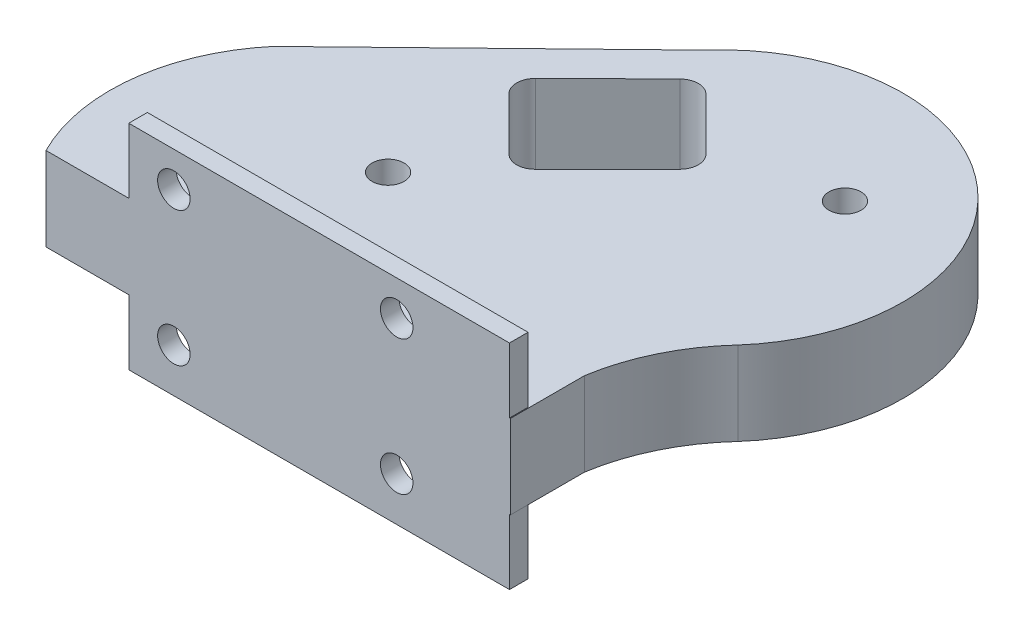
SolidWorks part; units mm, degrees
ref_plane "Front Plane" through (0, 0, 0) normal (0, 0, 1) x (1, 0, 0)
ref_plane "Top Plane" through (0, 0, 0) normal (0, 1, 0) x (1, 0, 0)
ref_plane "Right Plane" through (0, 0, 0) normal (1, 0, 0) x (0, 0, -1)
sketch "Sketch1" plane through (0, 0, 0) normal (0, 1, 0) x (1, 0, 0)
  line L0 (0, 0) -> (50, 0)
  line L1 (2.5356, 21.9463) -> (26.2158, 44.9299)
  line L2 (50, 0) -> (50, 8)
  arc A0 (0, 0) -> (2.5356, 21.9463) centre (17.8501, 9.0572) cw
  arc A1 (26.2158, 44.9299) -> (55.3976, 19.1107) centre (40.8067, 32.0203) cw
  arc A4 (50, 8) -> (55.3976, 19.1107) centre (71.1751, 4.5796) cw
  dimension "D1" = 50
  dimension "D2" = 33
extrude "Boss-Extrude1" add sketch "Sketch1" along normal blind 9
sketch "Sketch2" plane through (0, 0, 0) normal (0, 0, 1) x (1, 0, 0)
  line L0 (26.2158, 0) -> (60.2888, 0) construction
  line L1 (0, 4.5) -> (-11.7674, 4.5) construction
  line L2 (8.913, -7) -> (49.913, -7)
  line L3 (8.913, -7) -> (8.913, 0)
  line L4 (8.913, 0) -> (49.913, 0)
  line L5 (49.913, -7) -> (49.913, 0)
  line L6 (0, 9) -> (0, 0) construction
  line L7 (8.913, 9) -> (49.913, 9)
  line L8 (49.913, 16) -> (49.913, 9)
  line L9 (8.913, 16) -> (49.913, 16)
  line L10 (8.913, 16) -> (8.913, 9)
  dimension "D1" = 41
  dimension "D2" = 7
extrude "Boss-Extrude2" add sketch "Sketch2" against normal blind 2
sketch "Sketch3" plane through (0, 0, -2) normal (0, 0, -1) x (-1, 0, 0)
  circle A0 centre (-13.7694, -2.2635) radius 1.75
  circle A1 centre (-37.7694, -2.2635) radius 1.75
  circle A2 centre (-37.7694, 12.2365) radius 1.75
  circle A3 centre (-13.7694, 12.2365) radius 1.75
  dimension "D1" = 2
  dimension "D2" = 2
extrude "Cut-Extrude1" cut sketch "Sketch3" against normal blind 2
sketch "Sketch5" plane through (0, 9, 0) normal (0, 1, 0) x (1, 0, 0)
  circle A0 centre (20.4485, 16.3927) radius 1.725
  circle A1 centre (47.741, 38.3042) radius 1.725
  dimension "D1" = 35
  dimension "D2" = 3.45
extrude "Cut-Extrude4" cut sketch "Sketch5" against normal up to surface (9 mm away) up to face at (31.0592, 0, -11.3356)
sketch "Sketch6" plane through (0, 9, 0) normal (0, 1, 0) x (1, 0, 0)
  line L0 (18.2008, 31.6595) -> (28.8762, 42.1969)
  line L5 (28.8762, 42.1969) -> (37.2925, 33.7806)
  line L6 (37.2925, 33.7806) -> (26.6861, 23.1742)
  line L7 (26.6861, 23.1742) -> (18.2008, 31.6595)
  dimension "D1" = 15
  dimension "D2" = 12
extrude "Cut-Extrude5" cut sketch "Sketch6" against normal up to surface (9 mm away) up to face at (20.4485, 0, -18.1177)
fillet "Fillet1" radius 2 4 edges at (37.2925, 4.5, -33.7806) (26.6861, 4.5, -23.1742) (18.2008, 4.5, -31.6595) (28.8762, 4.5, -42.1969)
